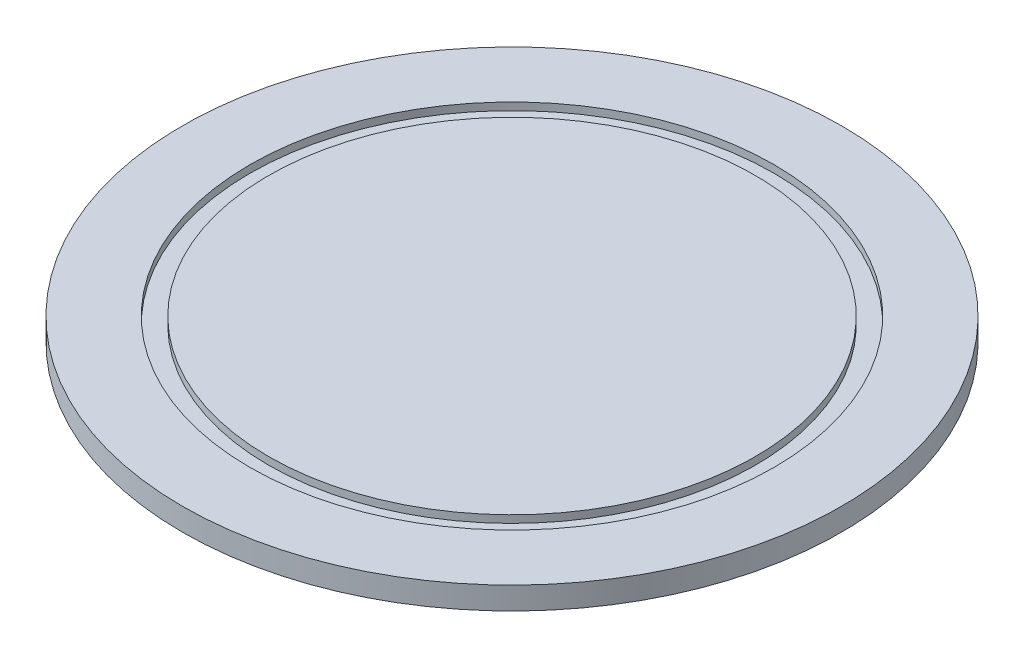
SolidWorks part; units mm, degrees
ref_plane "Front Plane" through (0, 0, 0) normal (0, 0, 1) x (1, 0, 0)
ref_plane "Top Plane" through (0, 0, 0) normal (0, 1, 0) x (1, 0, 0)
ref_plane "Right Plane" through (0, 0, 0) normal (1, 0, 0) x (0, 0, -1)
sketch "Sketch1" plane through (0, 0, 0) normal (0, 1, 0) x (1, 0, 0)
  circle A0 centre (0, 0) radius 440
  dimension "D1" = 880
extrude "Boss-Extrude1" add sketch "Sketch1" along normal mid plane 30
sketch "Sketch2" plane through (0, 15, 0) normal (0, 1, 0) x (1, 0, 0)
  circle A0 centre (0, 0) radius 325
  circle A1 centre (0, 0) radius 350
  dimension "D1" = 650
  dimension "D2" = 700
extrude "Cut-Extrude1" cut sketch "Sketch2" against normal blind 10
